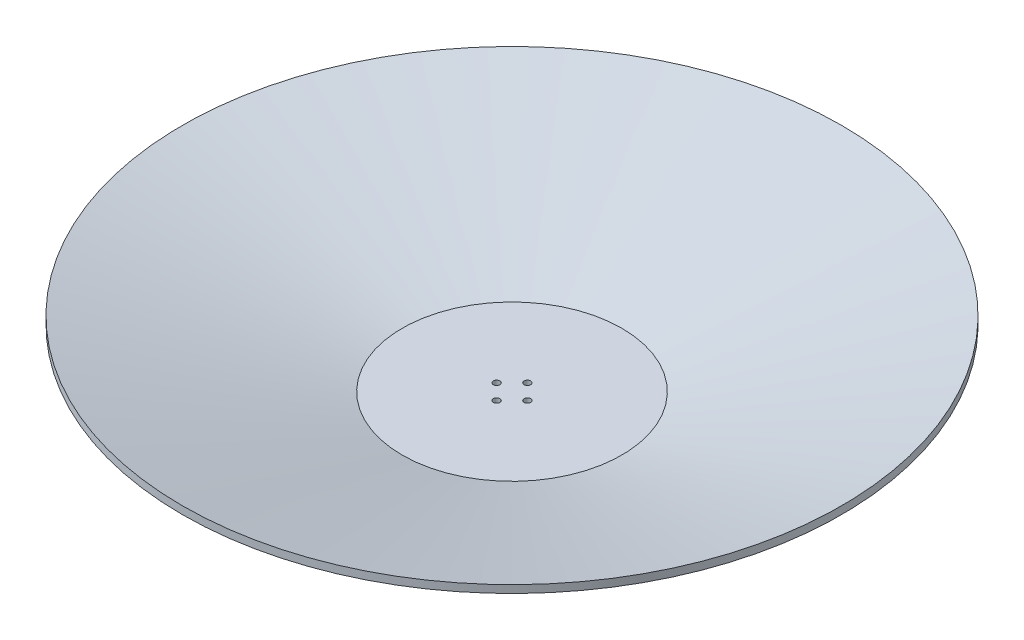
SolidWorks part; units mm, degrees
ref_plane "Front Plane" through (0, 0, 0) normal (0, 0, 1) x (1, 0, 0)
ref_plane "Top Plane" through (0, 0, 0) normal (0, 1, 0) x (1, 0, 0)
ref_plane "Right Plane" through (0, 0, 0) normal (1, 0, 0) x (0, 0, -1)
sketch "Sketch2" plane through (0, 0, 0) normal (0, 0, 1) x (1, 0, 0)
  line L0 (0, 0) -> (35, 0)
  line L4 (0, 7.2266) -> (0, 0)
  line L5 (0, 7.2266) -> (0, 20)
  line L8 (150, 46.5) -> (43.2341, 9.4894)
  line L9 (0, 20) -> (50, 20)
  line L10 (50, 20) -> (150, 50)
  line L12 (150, 46.5) -> (150, 50)
  line L13 (43.2341, 9.4894) -> (35, 0)
  dimension "D1" = 35
  dimension "D2" = 3.5
  dimension "D3" = 50
  dimension "D4" = 20
  dimension "D5" = 150
  dimension "D6" = 12.5
  dimension "D7" = 50
revolve "Revolve1" add sketch "Sketch2" angle 360 about L5
sketch "Sketch3" plane through (0, 0, 0) normal (0, -1, 0) x (1, 0, 0)
  circle A0 centre (0, 7) radius 1.5
  circle A1 centre (7, 0) radius 1.5
  circle A2 centre (0, -7) radius 1.5
  circle A3 centre (-7, 0) radius 1.5
  point P12 (0, 0)
  dimension "D1" = 7
  dimension "D3" = 3
  dimension "D2" = 4
extrude "Cut-Extrude1" cut sketch "Sketch3" against normal through all
sketch "Sketch4" plane through (0, 0, 0) normal (0, -1, 0) x (1, 0, 0)
  circle A0 centre (0, 0) radius 30
  dimension "D1" = 60
extrude "Cut-Extrude2" cut sketch "Sketch4" against normal blind 15
sketch "Sketch5" plane through (0, 15, 0) normal (0, -1, 0) x (1, 0, 0)
  line L1 (-29, -13) -> (29, -13)
  line L2 (-29, -13) -> (-29, 13)
  line L3 (-29, 13) -> (29, 13)
  line L4 (29, -13) -> (29, 13)
  line L5 (-29, -13) -> (29, 13) construction
  line L6 (-29, 13) -> (29, -13) construction
  circle A1 centre (0, 0) radius 30
  circle A2 centre (0, 0) radius 30
  dimension "D2" = 26
  dimension "D3" = 58
  dimension "D1" = 0
extrude "Cut-Extrude3" cut sketch "Sketch5" along normal through all contours L2 L1 L4 L3
move or copy body "Body-Move/Copy1" bodies to move or copy 104 copy no translate (0, -15, 0) parameters "D1"=0, "D2"=15, "D3"=0
